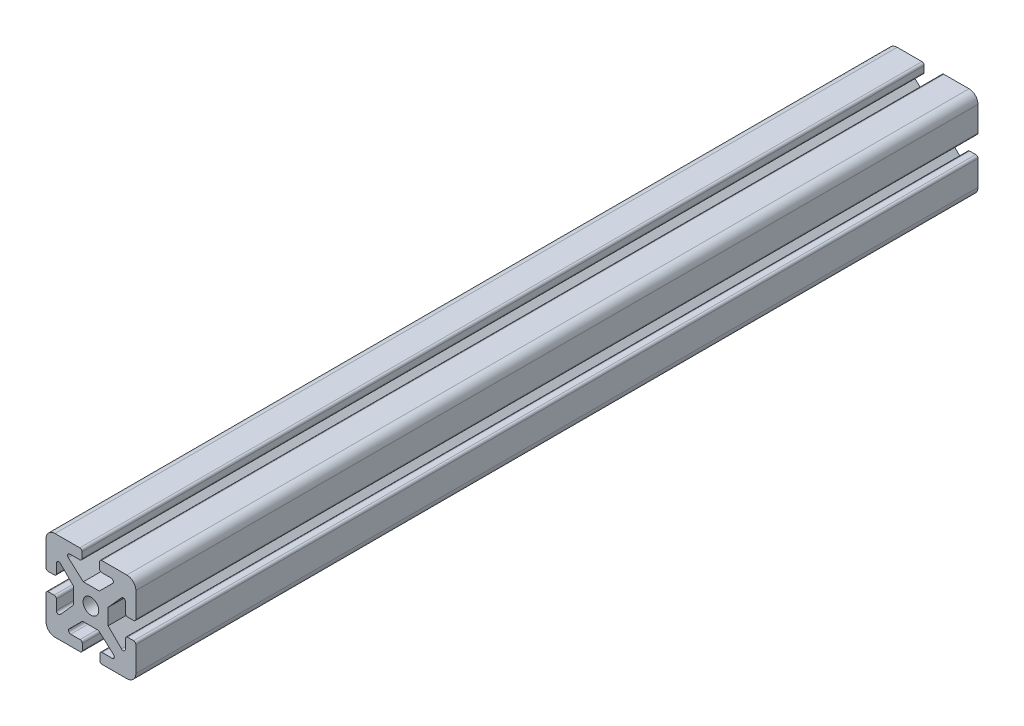
SolidWorks part; units mm, degrees
ref_plane "Front Plane" through (0, 0, 0) normal (0, 0, 1) x (1, 0, 0)
ref_plane "Top Plane" through (0, 0, 0) normal (0, 1, 0) x (1, 0, 0)
ref_plane "Right Plane" through (0, 0, 0) normal (1, 0, 0) x (0, 0, -1)
sketch "Sketch2" plane through (0, 0, 0) normal (0, 0, 1) x (1, 0, 0)
  line L0 (46.607, 139.3199) -> (233.0351, 139.3199) construction
  line L1 (0, 40) -> (40, 0) construction
  line L2 (0, 0) -> (40, 0) construction
  line L3 (0, 0) -> (0, 40) construction
  line L4 (0, 40) -> (40, 40) construction
  line L5 (40, 0) -> (40, 40) construction
  line L6 (0, 0) -> (40, 40) construction
  line L7 (19.4883, 27.6847) -> (23.7499, 27.6847)
  line L8 (23.7499, 27.6847) -> (29.6997, 33.625)
  line L9 (28.9931, 35.3327) -> (24.8456, 35.3327)
  line L10 (23.8456, 36.3327) -> (23.8456, 39)
  line L11 (24.8456, 40) -> (36, 40)
  line L12 (40, 36) -> (40, 24.9611)
  line L13 (39, 23.9611) -> (36.3883, 23.9611)
  line L14 (35.3883, 24.9611) -> (35.3883, 29.4086)
  line L15 (33.6417, 30.0739) -> (27.6847, 23.3888)
  line L16 (27.6847, 23.3888) -> (27.6847, 20.5117)
  line L17 (27.6847, 16.2501) -> (33.625, 10.3003)
  line L18 (30.0739, 6.3583) -> (23.3888, 12.3153)
  line L19 (27.6847, 20.5117) -> (27.6847, 16.2501)
  line L20 (35.3327, 11.0069) -> (35.3327, 15.1544)
  line L21 (36.3327, 16.1544) -> (39, 16.1544)
  line L22 (40, 15.1544) -> (40, 4)
  line L23 (36, 0) -> (24.9611, 0)
  line L24 (23.9611, 1) -> (23.9611, 3.6117)
  line L25 (24.9611, 4.6117) -> (29.4086, 4.6117)
  line L26 (23.3888, 12.3153) -> (20.5117, 12.3153)
  line L27 (16.2501, 12.3153) -> (10.3003, 6.375)
  line L28 (6.3583, 9.9261) -> (12.3153, 16.6112)
  line L29 (20.5117, 12.3153) -> (16.2501, 12.3153)
  line L30 (11.0069, 4.6673) -> (15.1544, 4.6673)
  line L31 (16.1544, 3.6673) -> (16.1544, 1)
  line L32 (15.1544, 0) -> (4, 0)
  line L33 (0, 4) -> (0, 15.0389)
  line L34 (1, 16.0389) -> (3.6117, 16.0389)
  line L35 (4.6117, 15.0389) -> (4.6117, 10.5914)
  line L36 (12.3153, 16.6112) -> (12.3153, 19.4883)
  line L37 (12.3153, 23.7499) -> (6.375, 29.6997)
  line L38 (9.9261, 33.6417) -> (16.6112, 27.6847)
  line L39 (12.3153, 19.4883) -> (12.3153, 23.7499)
  line L40 (4.6673, 28.9931) -> (4.6673, 24.8456)
  line L41 (3.6673, 23.8456) -> (1, 23.8456)
  line L42 (0, 24.8456) -> (0, 36)
  line L43 (4, 40) -> (15.0389, 40)
  line L44 (16.0389, 39) -> (16.0389, 36.3883)
  line L45 (15.0389, 35.3883) -> (10.5914, 35.3883)
  line L46 (16.6112, 27.6847) -> (19.4883, 27.6847)
  circle A1 centre (20, 20) radius 3.4925
  arc A2 (40, 24.9611) -> (39, 23.9611) centre (39, 24.9611) cw
  arc A3 (36.3883, 23.9611) -> (35.3883, 24.9611) centre (36.3883, 24.9611) cw
  arc A4 (24.8456, 35.3327) -> (23.8456, 36.3327) centre (24.8456, 36.3327) cw
  arc A5 (23.8456, 39) -> (24.8456, 40) centre (24.8456, 39) cw
  arc A6 (29.6997, 33.625) -> (28.9931, 35.3327) centre (28.9931, 34.3327) ccw
  arc A7 (35.3883, 29.4086) -> (33.6417, 30.0739) centre (34.3883, 29.4086) ccw
  arc A8 (40, 36) -> (36, 40) centre (36, 36) ccw
  arc A9 (35.3327, 15.1544) -> (36.3327, 16.1544) centre (36.3327, 15.1544) cw
  arc A10 (39, 16.1544) -> (40, 15.1544) centre (39, 15.1544) cw
  arc A11 (36, 0) -> (40, 4) centre (36, 4) ccw
  arc A12 (24.9611, 0) -> (23.9611, 1) centre (24.9611, 1) cw
  arc A13 (23.9611, 3.6117) -> (24.9611, 4.6117) centre (24.9611, 3.6117) cw
  arc A14 (29.4086, 4.6117) -> (30.0739, 6.3583) centre (29.4086, 5.6117) ccw
  arc A15 (33.625, 10.3003) -> (35.3327, 11.0069) centre (34.3327, 11.0069) ccw
  arc A16 (15.1544, 4.6673) -> (16.1544, 3.6673) centre (15.1544, 3.6673) cw
  arc A17 (16.1544, 1) -> (15.1544, 0) centre (15.1544, 1) cw
  arc A18 (0, 4) -> (4, 0) centre (4, 4) ccw
  arc A19 (0, 15.0389) -> (1, 16.0389) centre (1, 15.0389) cw
  arc A20 (3.6117, 16.0389) -> (4.6117, 15.0389) centre (3.6117, 15.0389) cw
  arc A21 (4.6117, 10.5914) -> (6.3583, 9.9261) centre (5.6117, 10.5914) ccw
  arc A22 (10.3003, 6.375) -> (11.0069, 4.6673) centre (11.0069, 5.6673) ccw
  arc A23 (4.6673, 24.8456) -> (3.6673, 23.8456) centre (3.6673, 24.8456) cw
  arc A24 (1, 23.8456) -> (0, 24.8456) centre (1, 24.8456) cw
  arc A25 (4, 40) -> (0, 36) centre (4, 36) ccw
  arc A26 (15.0389, 40) -> (16.0389, 39) centre (15.0389, 39) cw
  arc A27 (16.0389, 36.3883) -> (15.0389, 35.3883) centre (15.0389, 36.3883) cw
  arc A28 (10.5914, 35.3883) -> (9.9261, 33.6417) centre (10.5914, 34.3883) ccw
  arc A29 (6.375, 29.6997) -> (4.6673, 28.9931) centre (5.6673, 28.9931) ccw
  point P24 (40, 23.9611)
  point P31 (23.8456, 40)
  dimension "D1" = 40
  dimension "D3" = 1
  dimension "D4" = 4
  dimension "D2" = 40
  dimension "D5" = 4
extrude "Boss-Extrude1" add sketch "Sketch2" along normal blind 375
